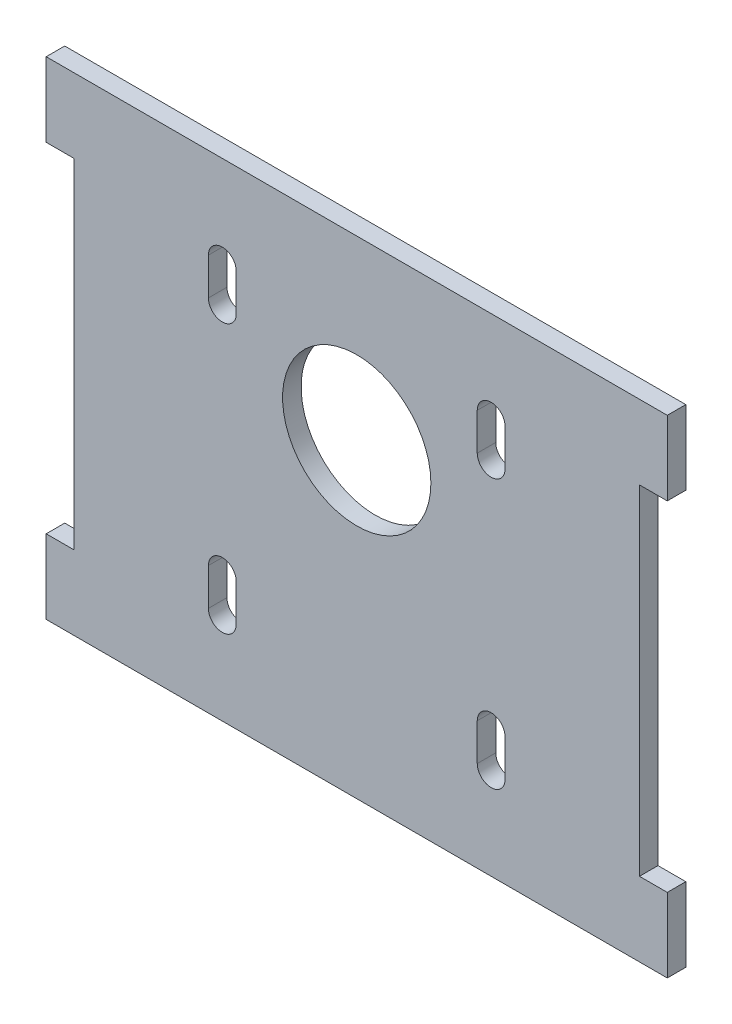
SolidWorks part; units mm, degrees
ref_plane "Front Plane" through (0, 0, 0) normal (0, 0, 1) x (1, 0, 0)
ref_plane "Top Plane" through (0, 0, 0) normal (0, 1, 0) x (1, 0, 0)
ref_plane "Right Plane" through (0, 0, 0) normal (1, 0, 0) x (0, 0, -1)
sketch "Sketch2" plane through (0, 0, 0) normal (0, 0, 1) x (1, 0, 0)
  line L0 (0, -106.3146) -> (0, 60.5946) construction
  line L1 (-106.3625, 60.5946) -> (106.3625, 60.5946)
  line L2 (-106.3625, 60.5946) -> (-106.3625, -106.3146)
  line L3 (-106.3625, -106.3146) -> (106.3625, -106.3146)
  line L4 (106.3625, 60.5946) -> (106.3625, -106.3146)
  line L5 (106.3625, -134.9375) -> (106.3625, -109.5375) construction
  arc A0 (47.7494, 29.4794) -> (-47.7494, 29.4794) centre (0, -167.132) ccw construction
  arc A1 (-47.7494, -75.1994) -> (47.7494, -75.1994) centre (0, 121.412) ccw construction
  point P6 (0, 35.1946)
  point P11 (0, -80.9146)
  dimension "D1" = 25.4
  dimension "D2" = 25.4
extrude "Extrude1" add sketch "Sketch2" along normal blind 6.35
sketch "Sketch3" plane through (0, 0, 6.35) normal (0, 0, 1) x (1, 0, 0)
  line L0 (46.0375, -75.2475) -> (46.0375, -62.5475) construction
  line L1 (50.8, -75.2475) -> (50.8, -62.5475)
  line L2 (41.275, -75.2475) -> (41.275, -62.5475)
  line L3 (46.0375, 16.8275) -> (46.0375, 29.5275) construction
  line L4 (50.8, 16.8275) -> (50.8, 29.5275)
  line L5 (41.275, 16.8275) -> (41.275, 29.5275)
  line L6 (-46.0375, 16.8275) -> (-46.0375, 29.5275) construction
  line L7 (-41.275, 16.8275) -> (-41.275, 29.5275)
  line L8 (-50.8, 16.8275) -> (-50.8, 29.5275)
  line L9 (-46.0375, -75.2475) -> (-46.0375, -62.5475) construction
  line L10 (-41.275, -75.2475) -> (-41.275, -62.5475)
  line L11 (-50.8, -75.2475) -> (-50.8, -62.5475)
  arc A0 (50.8, -75.2475) -> (41.275, -75.2475) centre (46.0375, -75.2475) cw
  arc A1 (41.275, -62.5475) -> (50.8, -62.5475) centre (46.0375, -62.5475) cw
  arc A2 (50.8, 16.8275) -> (41.275, 16.8275) centre (46.0375, 16.8275) cw
  arc A3 (41.275, 29.5275) -> (50.8, 29.5275) centre (46.0375, 29.5275) cw
  arc A4 (-41.275, 16.8275) -> (-50.8, 16.8275) centre (-46.0375, 16.8275) cw
  arc A5 (-50.8, 29.5275) -> (-41.275, 29.5275) centre (-46.0375, 29.5275) cw
  arc A6 (-41.275, -75.2475) -> (-50.8, -75.2475) centre (-46.0375, -75.2475) cw
  arc A7 (-50.8, -62.5475) -> (-41.275, -62.5475) centre (-46.0375, -62.5475) cw
  circle A8 centre (-46.0375, -68.8975) radius 3.175 construction
  circle A9 centre (46.0375, -68.8975) radius 3.175 construction
  circle A10 centre (46.0375, 23.1775) radius 3.175 construction
  circle A11 centre (-46.0375, 23.1775) radius 2.5565 construction
  circle A12 centre (0, 0) radius 25.4
  point P6 (46.0375, -68.8975)
  point P13 (46.0375, 23.1775)
  point P20 (-46.0375, 23.1775)
  point P27 (-46.0375, -68.8975)
  dimension "D1" = 4.7625
  dimension "D3" = 4.7625
  dimension "D5" = 4.7625
  dimension "D7" = 4.7625
  dimension "D9" = 50.8
  dimension "D2" = 12.7
  dimension "D4" = 12.7
  dimension "D6" = 12.7
  dimension "D8" = 12.7
extrude "Cut-Extrude1" cut sketch "Sketch3" against normal up to next
sketch "Sketch4" plane through (0, 0, 6.35) normal (0, 0, 1) x (1, 0, 0)
  line L0 (-106.3625, 60.5946) -> (-106.3625, -106.3146) construction
  line L1 (-106.3625, -80.9146) -> (-96.8375, -80.9146)
  line L2 (-106.3625, -80.9146) -> (-106.3625, 35.1946)
  line L3 (-106.3625, 35.1946) -> (-96.8375, 35.1946)
  line L4 (-96.8375, -80.9146) -> (-96.8375, 35.1946)
  line L5 (106.3625, -106.3146) -> (106.3625, 60.5946) construction
  line L6 (106.3625, -80.9146) -> (96.8375, -80.9146)
  line L7 (106.3625, -80.9146) -> (106.3625, 35.1946)
  line L8 (106.3625, 35.1946) -> (96.8375, 35.1946)
  line L9 (96.8375, -80.9146) -> (96.8375, 35.1946)
  line L10 (96.8375, -22.86) -> (-96.8375, -22.86) construction
  line L11 (106.3625, 60.5946) -> (-106.3625, 60.5946) construction
  line L12 (0, -106.3146) -> (0, 60.5946) construction
  line L13 (-106.3625, -106.3146) -> (106.3625, -106.3146) construction
  point P20 (0, -22.86)
  dimension "D1" = 25.4
  dimension "D2" = 9.525
extrude "Cut-Extrude2" cut sketch "Sketch4" against normal up to next
